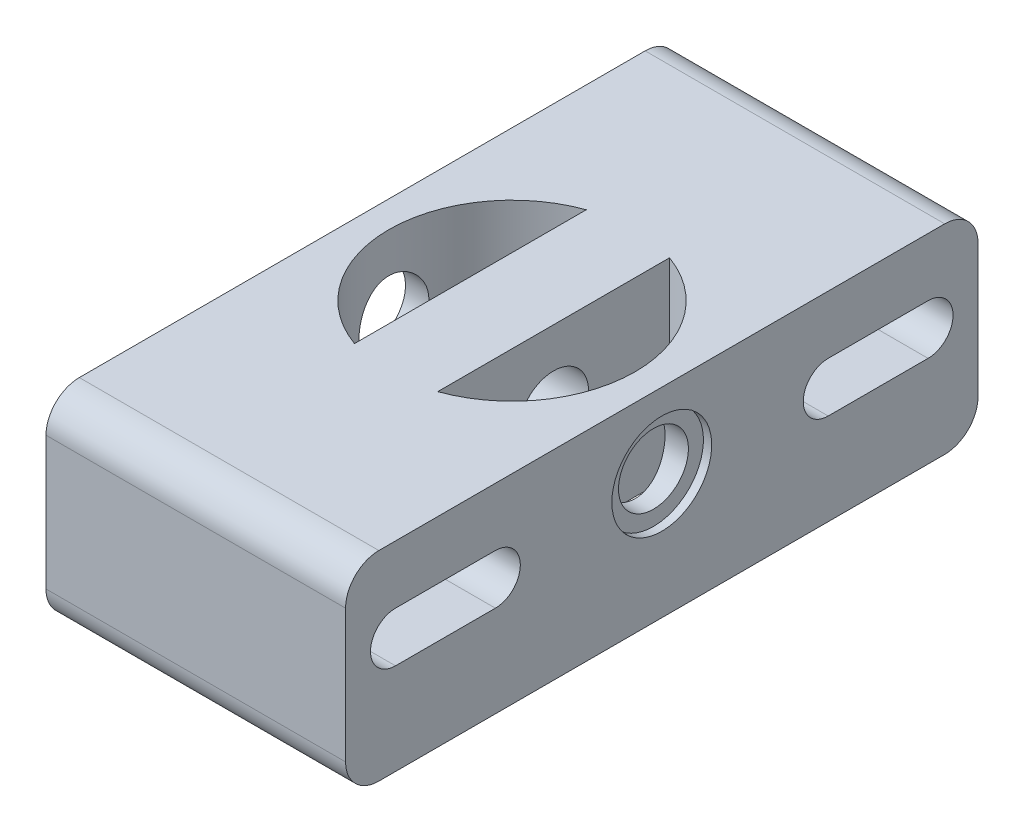
SolidWorks part; units mm, degrees
ref_plane "前视基准面" through (0, 0, 0) normal (0, 0, 1) x (1, 0, 0)
ref_plane "上视基准面" through (0, 0, 0) normal (0, 1, 0) x (1, 0, 0)
ref_plane "右视基准面" through (0, 0, 0) normal (1, 0, 0) x (0, 0, -1)
sketch "草图1" plane through (0, 0, 0) normal (0, 1, 0) x (1, 0, 0)
  line L0 (-10.0788, 0) -> (13.4422, 0) construction
  line L1 (-9, 19) -> (9, 19)
  line L2 (-9, 19) -> (-9, -19)
  line L3 (-9, -19) -> (9, -19)
  line L4 (9, 19) -> (9, -19)
  line L13 (0, 20.8509) -> (0, -19.4544) construction
  line L14 (0, 19) -> (0, -19) construction
  line L15 (2.5, 6.9649) -> (2.5, -6.9649)
  line L16 (-2.5, 6.9649) -> (-2.5, -6.9649)
  arc A4 (-2.5, 6.9649) -> (-2.5, -6.9649) centre (0, 0) ccw
  arc A5 (2.5, -6.9649) -> (2.5, 6.9649) centre (0, 0) ccw
  point P0 (0, 0)
  point P6 (0, 0)
  point P14 (9, 0)
  dimension "D3" = 14.8
  dimension "D1" = 18
  dimension "D2" = 38
  dimension "D4" = 2.5
extrude "凸台-拉伸1" add sketch "草图1" along normal blind 12
sketch "草图2" plane through (-9, 0, 0) normal (-1, 0, 0) x (0, 0, 1)
  line L0 (-19, 12) -> (19, 12) construction
  circle A0 centre (0, 7.5) radius 2.1
  dimension "D1" = 4.2
  dimension "D2" = 4.5
extrude "切除-拉伸1" cut sketch "草图2" against normal through all
sketch "草图3" plane through (-9, 0, 0) normal (-1, 0, 0) x (0, 0, 1)
  circle A0 centre (0, 7.5) radius 3
extrude "切除-拉伸2" cut sketch "草图3" against normal blind 0.5
mirror "镜向1" about plane through (0, 0, 0) normal (1, 0, 0) of "切除-拉伸2"
sketch "草图4" plane through (-9, 0, 0) normal (-1, 0, 0) x (0, 0, 1)
  line L0 (0, 12.5416) -> (0, -4.1511) construction
  line L1 (-16, 8.5) -> (-10, 8.5)
  line L2 (-10, 5.5) -> (-16, 5.5)
  line L3 (-19, 0) -> (19, 0) construction
  line L4 (-19, 12) -> (-19, 0) construction
  line L5 (10, 5.5) -> (16, 5.5)
  line L6 (16, 8.5) -> (10, 8.5)
  arc A0 (-16, 8.5) -> (-16, 5.5) centre (-16, 7) ccw
  arc A1 (-10, 5.5) -> (-10, 8.5) centre (-10, 7) ccw
  arc A2 (10, 5.5) -> (10, 8.5) centre (10, 7) cw
  arc A3 (16, 8.5) -> (16, 5.5) centre (16, 7) cw
  dimension "D1" = 1.5
  dimension "D2" = 7
  dimension "D3" = 3
  dimension "D4" = 6
extrude "切除-拉伸3" cut sketch "草图4" against normal through all
fillet "圆角1" radius 2 4 edges at (0, 12, 19) (0, 0, 19) (0, 0, -19) (0, 12, -19)
chamfer "倒角1" distance 0.6 angle 45 4 edges at (-7.4, 0, 0) (-2.5, 0, 0) (2.5, 0, 0) (7.4, 0, 0)
